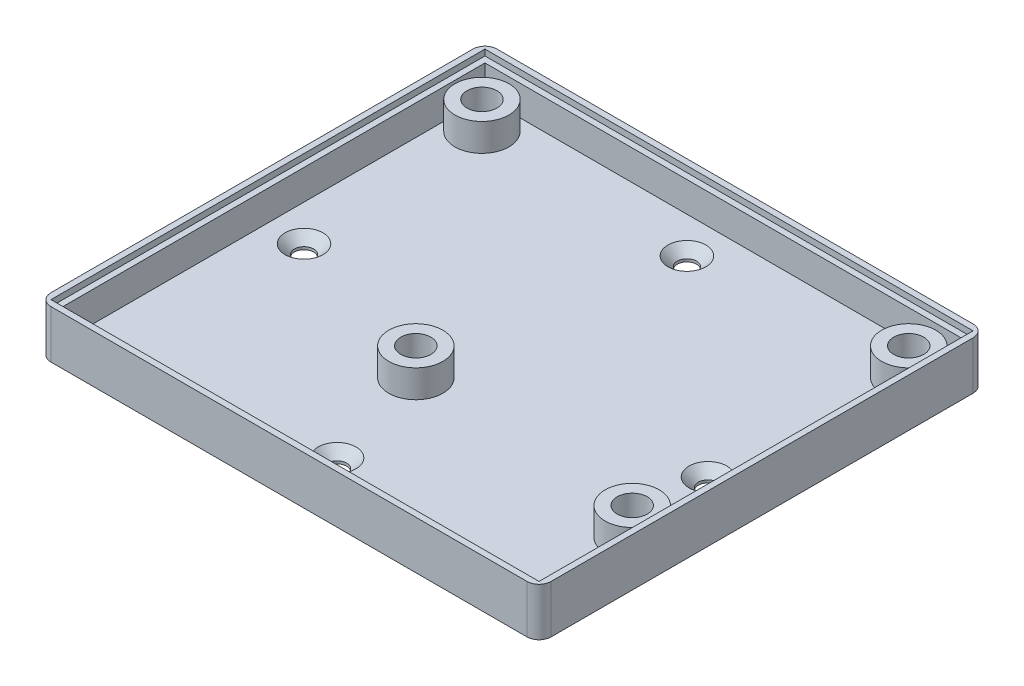
SolidWorks part; units mm, degrees
ref_plane "Front Plane" through (0, 0, 0) normal (0, 0, 1) x (1, 0, 0)
ref_plane "Top Plane" through (0, 0, 0) normal (0, 1, 0) x (1, 0, 0)
ref_plane "Right Plane" through (0, 0, 0) normal (1, 0, 0) x (0, 0, -1)
sketch "Sketch1" plane through (0, 0, 0) normal (0, 1, 0) x (1, 0, 0)
  line L1 (0, 0) -> (83.2, 0)
  line L2 (0, 0) -> (0, 74.2)
  line L3 (0, 74.2) -> (83.2, 74.2)
  line L4 (83.2, 0) -> (83.2, 74.2)
  dimension "D1" = 83.2
  dimension "D2" = 74.2
extrude "Boss-Extrude1" add sketch "Sketch1" along normal blind 8
shell "Shell1" thickness 2
sketch "Sketch2" plane through (0, 2, 0) normal (0, 1, 0) x (1, 0, 0)
  line L2 (2, 72.2) -> (2, 2) construction
  line L3 (81.2, 72.2) -> (2, 72.2) construction
  line L4 (2, 2) -> (81.2, 2) construction
  line L5 (81.2, 2) -> (81.2, 72.2) construction
  circle A0 centre (6.6, 67.1) radius 2.5
  circle A1 centre (6.6, 67.1) radius 4.5
  circle A2 centre (36.6, 26.1) radius 2.5
  circle A3 centre (36.6, 26.1) radius 4.5
  circle A4 centre (77.6, 67.1) radius 2.5
  circle A5 centre (77.6, 67.1) radius 4.5
  circle A6 centre (77.6, 21.1) radius 2.5
  circle A7 centre (77.6, 21.1) radius 4.5
  dimension "D1" = 4.6
  dimension "D3" = 5
  dimension "D4" = 9
  dimension "D5" = 5
  dimension "D6" = 34.6
  dimension "D7" = 24.1
  dimension "D8" = 9
  dimension "D9" = 3.6
  dimension "D10" = 5.1
  dimension "D11" = 5
  dimension "D12" = 9
  dimension "D13" = 3.6
  dimension "D15" = 5
  dimension "D16" = 9
  dimension "D2" = 5.1
  dimension "D14" = 19.1
extrude "Boss-Extrude2" add sketch "Sketch2" along normal offset from surface (4.6 mm away) 1.4 up to face at (41.6, 8, -37.1)
sketch "Sketch3" plane through (0, 8, 0) normal (0, 1, 0) x (1, 0, 0)
  line L7 (1, 73.2) -> (1, 1)
  line L8 (1, 1) -> (82.2, 1)
  line L9 (82.2, 1) -> (82.2, 73.2)
  line L10 (82.2, 73.2) -> (1, 73.2)
  line L11 (0, 74.2) -> (0, 0)
  line L12 (0, 0) -> (83.2, 0)
  line L13 (83.2, 0) -> (83.2, 74.2)
  line L14 (83.2, 74.2) -> (0, 74.2)
  line L15 (0, 74.2) -> (0, 0) construction
  line L16 (0, 0) -> (83.2, 0) construction
  line L17 (83.2, 0) -> (83.2, 74.2) construction
  line L18 (83.2, 74.2) -> (0, 74.2) construction
  dimension "D1" = 0
  dimension "D2" = 1
extrude "Cut-Extrude1" cut sketch "Sketch3" against normal blind 1
sketch "Sketch4" plane through (0, 2, 0) normal (0, 1, 0) x (1, 0, 0)
  circle A1 centre (6.6, 67.1) radius 2.5
  circle A2 centre (6.6, 67.1) radius 2.5
  circle A3 centre (77.6, 67.1) radius 2.5
  circle A4 centre (77.6, 67.1) radius 2.5
  circle A5 centre (36.6, 26.1) radius 2.5
  circle A6 centre (36.6, 26.1) radius 2.5
  circle A7 centre (77.6, 21.1) radius 2.5
  circle A8 centre (77.6, 21.1) radius 2.5
  dimension "D1" = 0
  dimension "D2" = 0
  dimension "D3" = 0
  dimension "D4" = 0
extrude "Boss-Extrude3" add sketch "Sketch4" along normal blind 0.5
hole_wizard "CSK for M3 Flat Head Machine Screw1" positions "Sketch5" profile "Sketch6" countersink size "M3" standard "ANSI Metric" end condition through all
sketch "Sketch5" plane through (0, 2, 0) normal (0, 1, 0) x (1, 0, 0)
  line L0 (0, 74.2) -> (0, 0) construction
  line L1 (0, 0) -> (83.2, 0) construction
  line L2 (81.2, 72.2) -> (2, 72.2) construction
  line L3 (83.2, 0) -> (83.2, 74.2) construction
  line L4 (83.2, 74.2) -> (0, 74.2) construction
  point P0 (41.6, 66.2)
  point P2 (8, 36.1)
  point P4 (75.2, 36.1)
  point P6 (41.6, 8)
  dimension "D1" = 8
  dimension "D2" = 36.1
  dimension "D3" = 36.1
  dimension "D4" = 36.1
  dimension "D5" = 8
  dimension "D6" = 8
  dimension "D7" = 8
  dimension "D8" = 41.6
  dimension "D9" = 41.6
  dimension "D10" = 41.6
sketch "Sketch6" plane through (41.6, 2, -66.2) normal (1, 0, 0) x (0, 0, 1)
  line L0 (0, 0) -> (0, 2)
  line L1 (0, 2) -> (1.6, 2)
  line L2 (1.6, 2) -> (1.6, 1.55)
  line L3 (1.6, 1.55) -> (3.15, 0)
  line L5 (3.15, 0) -> (0, 0)
  line L6 (-1.6, 1.55) -> (-3.15, 0) construction
  line L11 (0, -6.35) -> (0, 107.95) construction
  dimension "Thru Hole Dia." = 3.2
  dimension "Thru Hole Depth" = 2
  dimension "Near C'Sink Dia." = 6.3
  dimension "Near C'Sink Angle" = 90
fillet "Fillet1" radius 2 4 edges at (0, 4, -74.2) (83.2, 4, -74.2) (83.2, 4, 0) (0, 4, 0)
